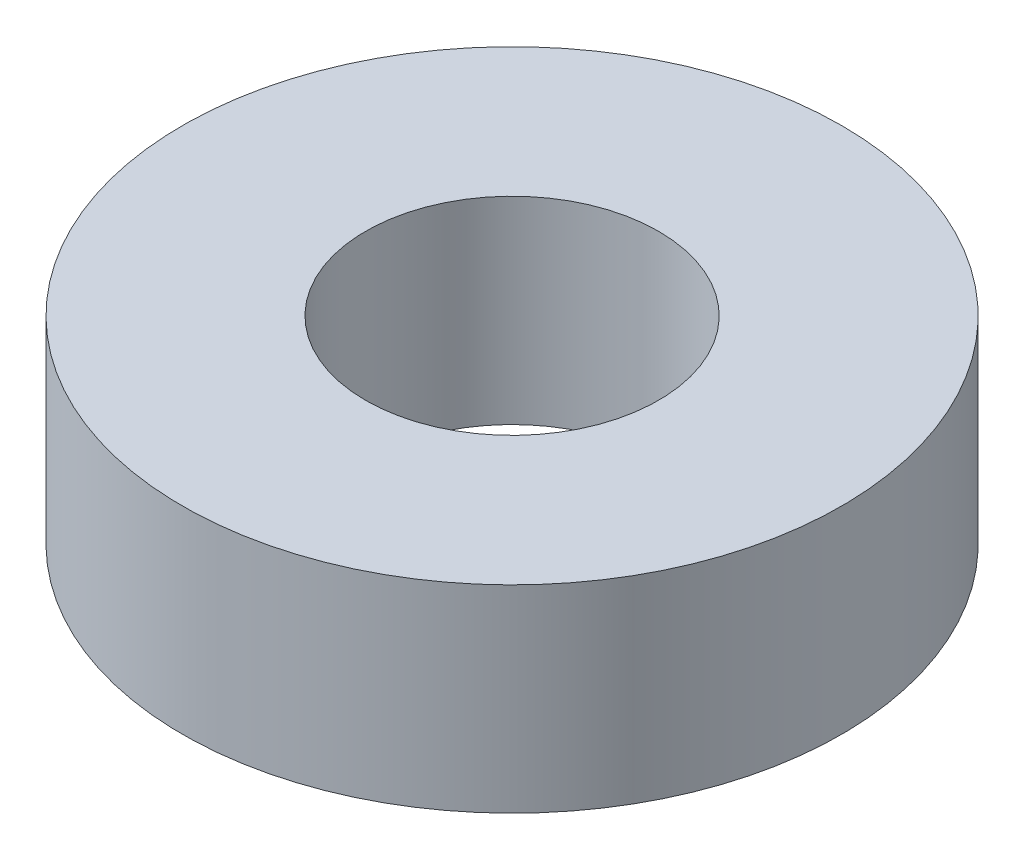
SolidWorks part; units mm, degrees
ref_plane "Plano frontal" through (0, 0, 0) normal (0, 0, 1) x (1, 0, 0)
ref_plane "Plano superior" through (0, 0, 0) normal (0, 1, 0) x (1, 0, 0)
ref_plane "Plano direito" through (0, 0, 0) normal (1, 0, 0) x (0, 0, -1)
sketch "Esboço1" plane through (0, 0, 0) normal (0, 1, 0) x (1, 0, 0)
  circle A0 centre (0, 0) radius 4.5
  circle A1 centre (0, 0) radius 2
  dimension "D1" = 9
  dimension "D2" = 4
extrude "Ressalto-extrusão1" add sketch "Esboço1" along normal blind 2.7
